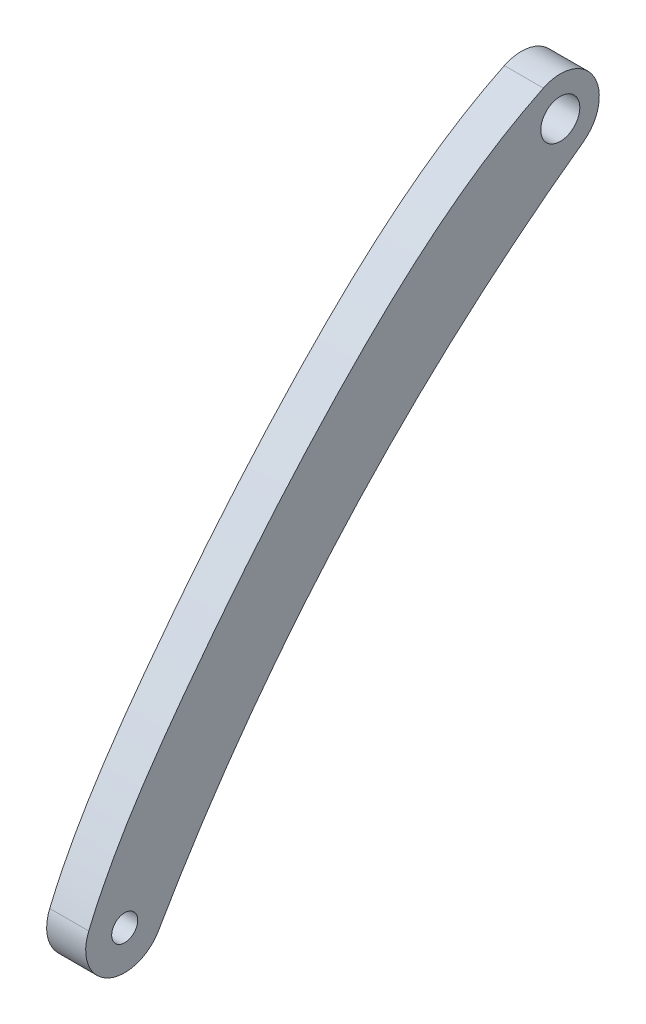
SolidWorks part; units mm, degrees
ref_plane "Front Plane" through (0, 0, 0) normal (1, 0, 0) x (0, 1, 0)
ref_plane "Top Plane" through (0, 0, 0) normal (0, 0, 1) x (0, 1, 0)
ref_plane "Right Plane" through (0, 0, 0) normal (0, 1, 0) x (-1, 0, 0)
sketch "Sketch1" plane through (0, 0, 0) normal (1, 0, 0) x (0, 1, 0)
  line L0 (34.9544, 81.6423) -> (174.7722, 81.6423) construction
  line L1 (65.8943, 10.0491) -> (83.7948, 55.6624) construction
  line L2 (83.7948, 55.6624) -> (52.1805, 74.3019) construction
  line L3 (52.1805, 74.3019) -> (65.8943, 10.0491) construction
  line L4 (83.7948, 55.6624) -> (128.0091, 98.9834) construction
  line L5 (128.0091, 98.9834) -> (90.89, 132.4822) construction
  line L6 (90.89, 132.4822) -> (75.2816, 94.0293) construction
  line L7 (75.2816, 94.0293) -> (83.7948, 55.6624) construction
  line L8 (52.1805, 74.3019) -> (39.1862, 111.4975) construction
  line L9 (39.1862, 111.4975) -> (90.89, 132.4822) construction
  line L10 (39.1862, 111.4975) -> (75.2816, 94.0293) construction
  line L11 (128.0091, 98.9834) -> (113.2816, 101.8293) construction
  dimension "D1" = 49
  dimension "D2" = 65.7
  dimension "D3" = 36.7
  dimension "D4" = 61.9
  dimension "D5" = 50
  dimension "D6" = 41.5
  dimension "D7" = 39.3
  dimension "D8" = 55.8
  dimension "D9" = 39.4
  dimension "D10" = 40.1
  dimension "D11" = 15
  dimension "D12" = 7.8
  dimension "D13" = 38
sketch "Sketch3" plane through (0, 0, 0) normal (1, 0, 0) x (0, 1, 0)
  circle A0 centre (52.1805, 74.3019) radius 10
  circle A2 centre (83.7948, 55.6624) radius 10
  arc A3 (118.15, 100.6563) -> (130.9207, 108.5501) centre (128.0091, 98.9834) ccw
  circle A5 centre (75.2816, 94.0293) radius 10
  circle A6 centre (39.1862, 111.4975) radius 10
  arc A7 (100.1088, 136.3569) -> (93.5623, 122.8459) centre (90.89, 132.4822) ccw
  circle A14 centre (39.1862, 111.4975) radius 1
  arc A19 (130.9207, 108.5501) -> (100.1088, 136.3569) centre (59.7936, 60.7105) ccw
  arc A20 (118.15, 100.6563) -> (93.5623, 122.8459) centre (59.7936, 60.7105) ccw
  circle A21 centre (90.89, 132.4822) radius 1
  circle A22 centre (128.0091, 98.9834) radius 1.5
  dimension "D1" = 20
  dimension "D2" = 2
  dimension "D3" = 2
  dimension "D4" = 15
  dimension "D5" = 3
extrude "Boss-Extrude2" add sketch "Sketch3" along normal blind 3 contours A20 A3 A19 A7 A22 A21
scale "Scale1" scale about centroid uniform scaling yes scale factor 2
sketch "Sketch4" plane through (-1.5, 0, 0) normal (-1, 0, 0) x (0, -1, 0)
  arc A0 (-68.2686, 142.7069) -> (-73.5804, 153.4417) centre (-71.2566, 147.91) ccw
  arc A1 (-150.8983, 83.5203) -> (-140.6246, 77.4079) centre (-145.4948, 80.9123) ccw
  arc A2 (-68.2686, 142.7069) -> (-140.6246, 77.4079) centre (46.5978, -57.3105) ccw
  arc A11 (-74.8925, 118.1311) -> (-115.5002, 81.4839) centre (-9.0639, 4.3666) ccw
  arc A12 (-74.8925, 118.1311) -> (-97.2133, 162.9515) centre (-71.2566, 147.91) ccw
  arc A13 (-97.2133, 162.9515) -> (-157.8031, 108.2711) centre (-9.0639, 4.3666) ccw
  arc A14 (-157.8031, 108.2711) -> (-115.5002, 81.4839) centre (-145.4948, 80.9123) ccw
  arc A15 (-74.8925, 118.1311) -> (-115.5002, 81.4839) centre (-9.0639, 4.3666) ccw
  arc A16 (-74.8925, 118.1311) -> (-97.2133, 162.9515) centre (-71.2566, 147.91) ccw
  arc A17 (-97.2133, 162.9515) -> (-157.8031, 108.2711) centre (-9.0639, 4.3666) ccw
  arc A18 (-157.8031, 108.2711) -> (-115.5002, 81.4839) centre (-145.4948, 80.9123) ccw
  spline S0 degree 3 poles (-150.8983, 83.5203) (-145.2052, 95.3159) (-127.7448, 114.8439) (-100.7779, 137.1611) (-82.3898, 149.7409) (-73.5804, 153.4417) knots 0 0 0 0 0.370027 0.730223 1 1 1 1
  point P1 (46.5978, -57.3105)
  point P10 (-97.882, 138.6953)
  point P12 (-126.9367, 114.277)
  point P14 (-150.8983, 83.5203)
  point P15 (-73.5804, 153.4417)
  arc M12 (-125.7766, 84.2581) -> (-76.6012, 128.6374) centre (-9.0639, 4.3666) cw
  arc M13 (-76.6012, 128.6374) -> (-89.6942, 155.6594) centre (-71.2566, 147.91) ccw
  arc M14 (-89.6942, 155.6594) -> (-151.3181, 100.0458) centre (-9.0639, 4.3666) ccw
  arc M15 (-151.3181, 100.0458) -> (-125.7766, 84.2581) centre (-145.4948, 80.9123) ccw
  dimension "D1" = 12
  dimension "D2" = 12
  dimension "D3" = 10
extrude "Cut-Extrude1" cut sketch "Sketch4" against normal through all both and the other way through all contours A1 S0 A0 A2 M15 M12 M13 M14 | A17 A18 A15 A16 M12 M15 M14 M13
